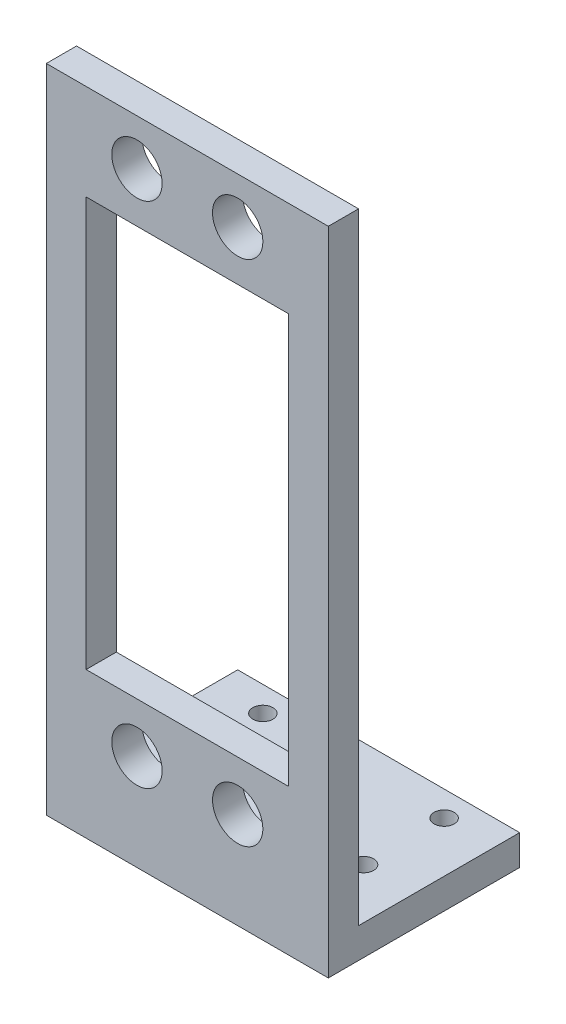
SolidWorks part; units mm, degrees
ref_plane "Front Plane" through (0, 0, 0) normal (0, 0, 1) x (1, 0, 0)
ref_plane "Top Plane" through (0, 0, 0) normal (0, 1, 0) x (1, 0, 0)
ref_plane "Right Plane" through (0, 0, 0) normal (1, 0, 0) x (0, 0, -1)
sketch "Sketch1" plane through (0, 0, 0) normal (0, 0, 1) x (1, 0, 0)
  line L2 (0, 0) -> (0, 64.64)
  line L4 (28, 0) -> (28, 64.64)
  line L10 (0, 64.64) -> (28, 64.64)
  line L11 (0, 0) -> (28, 0)
  dimension "D1" = 64.64
  dimension "D2" = 28
extrude "Boss-Extrude1" add sketch "Sketch1" along normal blind 3
sketch "Sketch2" plane through (0, 0, 3) normal (0, 0, 1) x (1, 0, 0)
  line L0 (9, 60.07) -> (19, 60.07) construction
  line L1 (9, 9.57) -> (19, 9.57) construction
  line L3 (28, 64.64) -> (0, 64.64) construction
  circle A0 centre (9, 9.57) radius 2.5
  circle A1 centre (19, 9.57) radius 2.5
  circle A2 centre (9, 60.07) radius 2.5
  circle A3 centre (19, 60.07) radius 2.5
  point P11 (14, 9.57)
  point P21 (14, 64.64)
  dimension "D2" = 5
  dimension "D1" = 50.5
  dimension "D3" = 10
  dimension "D4" = 4.57
extrude "Cut-Extrude1" cut sketch "Sketch2" against normal through all
sketch "Sketch4" plane through (0, 0, 3) normal (0, 0, 1) x (1, 0, 0)
  line L11 (24.05, 55.14) -> (3.95, 55.14)
  line L12 (24.05, 55.14) -> (24.05, 14.5)
  line L13 (24.05, 14.5) -> (3.95, 14.5)
  line L14 (3.95, 55.14) -> (3.95, 14.5)
  line L16 (28, 64.64) -> (0, 64.64) construction
  circle A0 centre (19, 60.07) radius 2.5 construction
  circle A1 centre (19, 60.07) radius 2.5 construction
  point P6 (14, 14.5)
  point P12 (14, 64.64)
  dimension "D1" = 4.93
  dimension "D5" = 20.1
  dimension "D6" = 40.64
extrude "Cut-Extrude6" cut sketch "Sketch4" against normal blind 10
sketch "Sketch5" plane through (0, 0, 0) normal (0, 0, -1) x (-1, 0, 0)
  line L0 (-28, 0) -> (-28, 64.64) construction
  line L1 (0, 0) -> (-28, 0)
  line L2 (0, 0) -> (0, 3)
  line L3 (0, 3) -> (-28, 3)
  line L4 (-28, 0) -> (-28, 3)
  dimension "D1" = 3
extrude "Boss-Extrude2" add sketch "Sketch5" along normal blind 16
sketch "Sketch6" plane through (0, 3, 0) normal (0, 1, 0) x (1, 0, 0)
  line L0 (0, 16) -> (0, 0) construction
  line L1 (28, 16) -> (28, 0) construction
  line L2 (0, 16) -> (28, 16) construction
  circle A0 centre (5, 5.5) radius 1
  circle A1 centre (5, 13.5) radius 1
  circle A2 centre (23, 13.5) radius 1
  circle A3 centre (23, 5.5) radius 1
  dimension "D1" = 2
  dimension "D2" = 5
  dimension "D3" = 5
  dimension "D4" = 2.5
  dimension "D5" = 8
  dimension "D6" = 18
extrude "Cut-Extrude7" cut sketch "Sketch6" against normal blind 10
